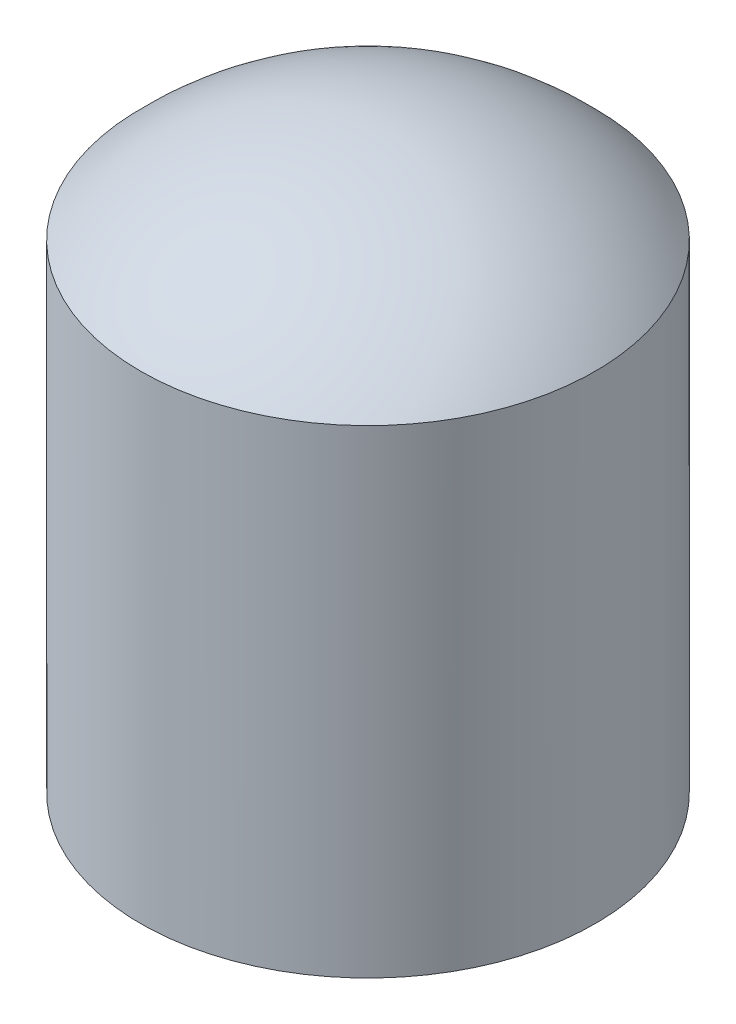
SolidWorks part; units mm, degrees
ref_plane "Front Plane" through (0, 0, 0) normal (0, 0, 1) x (1, 0, 0)
ref_plane "Top Plane" through (0, 0, 0) normal (0, 1, 0) x (1, 0, 0)
ref_plane "Right Plane" through (0, 0, 0) normal (1, 0, 0) x (0, 0, -1)
sketch "Sketch35" plane through (0, 0, 0) normal (1, 0, 0) x (0, 0, -1)
  line L0 (-17, 0) -> (-17, 40)
  line L1 (-19, 0) -> (-19, 40)
  line L2 (0, 0) -> (-29.6243, 0) construction
  line L3 (0, 0) -> (0, 48.1725) construction
  line L4 (-19, 40) -> (23.9757, 40) construction
  line L5 (-19, 0) -> (-17, 0)
  line L6 (0, 46.2488) -> (0, 48.1725)
  arc A0 (-19, 40) -> (0, 48.1725) centre (0, 22) cw
  arc A1 (-17, 40) -> (0, 46.2488) centre (0, 20) cw
  dimension "D1" = 17
  dimension "D2" = 2
  dimension "D3" = 40
  dimension "D4" = 2
  dimension "D5" = 20
revolve "Revolve1" add sketch "Sketch35" angle 360 about L6
